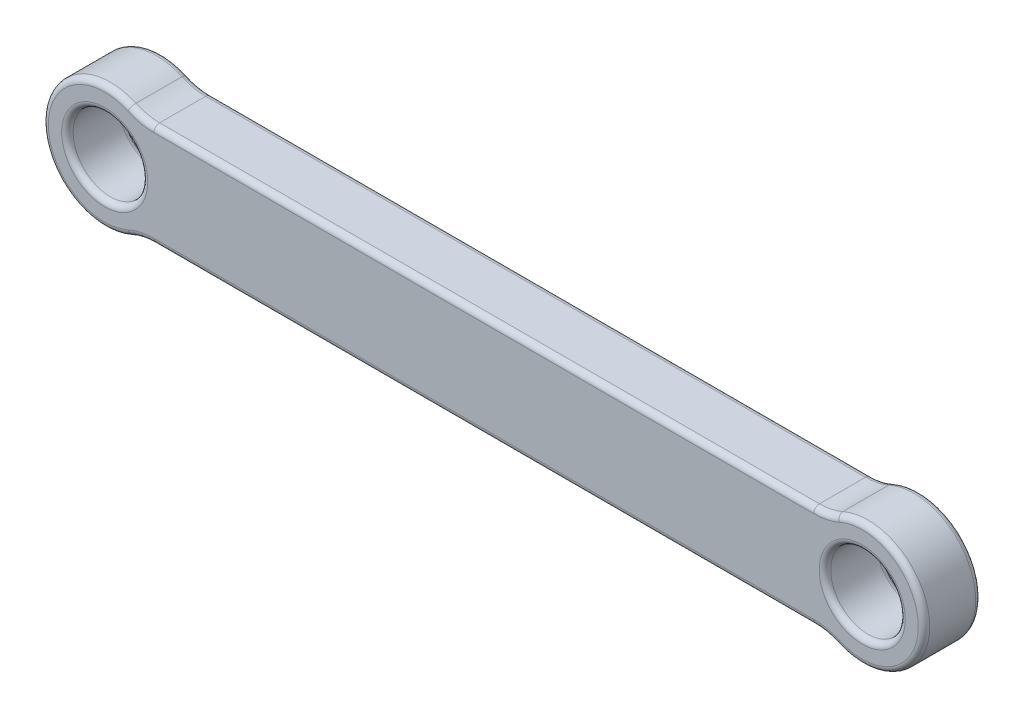
SolidWorks part; units mm, degrees
ref_plane "前视基准面" through (0, 0, 0) normal (0, 0, 1) x (1, 0, 0)
ref_plane "上视基准面" through (0, 0, 0) normal (0, 1, 0) x (1, 0, 0)
ref_plane "右视基准面" through (0, 0, 0) normal (1, 0, 0) x (0, 0, -1)
sketch "草图1" plane through (0, 0, 0) normal (0, 0, 1) x (1, 0, 0)
  line L0 (66, 0) -> (-66, 0) construction
  line L1 (60.0536, -8.964) -> (-59.9464, -8.964)
  line L3 (60.0536, 8.964) -> (-59.9464, 8.964)
  line L5 (75, -6) -> (-75, 6) construction
  line L6 (74.9504, 5.9669) -> (-75.0542, -5.9752) construction
  arc A0 (-59.9464, 8.964) -> (-59.9464, -8.964) centre (-66, 0) ccw
  arc A1 (60.0536, -8.964) -> (60.0536, 8.964) centre (66, 0) ccw
  point P0 (0, 0)
  point P9 (0, 0)
extrude "凸台-拉伸1" add sketch "草图1" along normal blind 10
sketch "草图2" plane through (0, 0, 10) normal (0, 0, 1) x (1, 0, 0)
  circle A0 centre (-66, 0) radius 6.5
  circle A1 centre (66, 0) radius 6.5
extrude "切除-拉伸1" cut sketch "草图2" against normal through all contours A1 | A0
fillet "圆角1" radius 10 4 edges at (60.0536, -8.964, 5) (-59.9464, -8.964, 5) (60.0536, 8.964, 5) (-59.9464, 8.964, 5)
fillet "圆角2" radius 1 20 edges at (59.639, 9.1824, 0) (0.0728, 8.964, 0) (-59.5247, 9.1891, 0) (-76.8167, 0, 0) (-59.5247, -9.1891, 0) (0.0728, -8.964, 0) (59.639, -9.1824, 0) (76.757, 0, 0) (-59.5, 0, 0) (72.5, 0, 0) (-59.5247, -9.1891, 10) (-76.8167, 0, 10) (-59.5247, 9.1891, 10) (0.0728, 8.964, 10) (59.639, 9.1824, 10) (76.757, 0, 10) (59.639, -9.1824, 10) (0.0728, -8.964, 10) (-59.5, 0, 10) (72.5, 0, 10)
